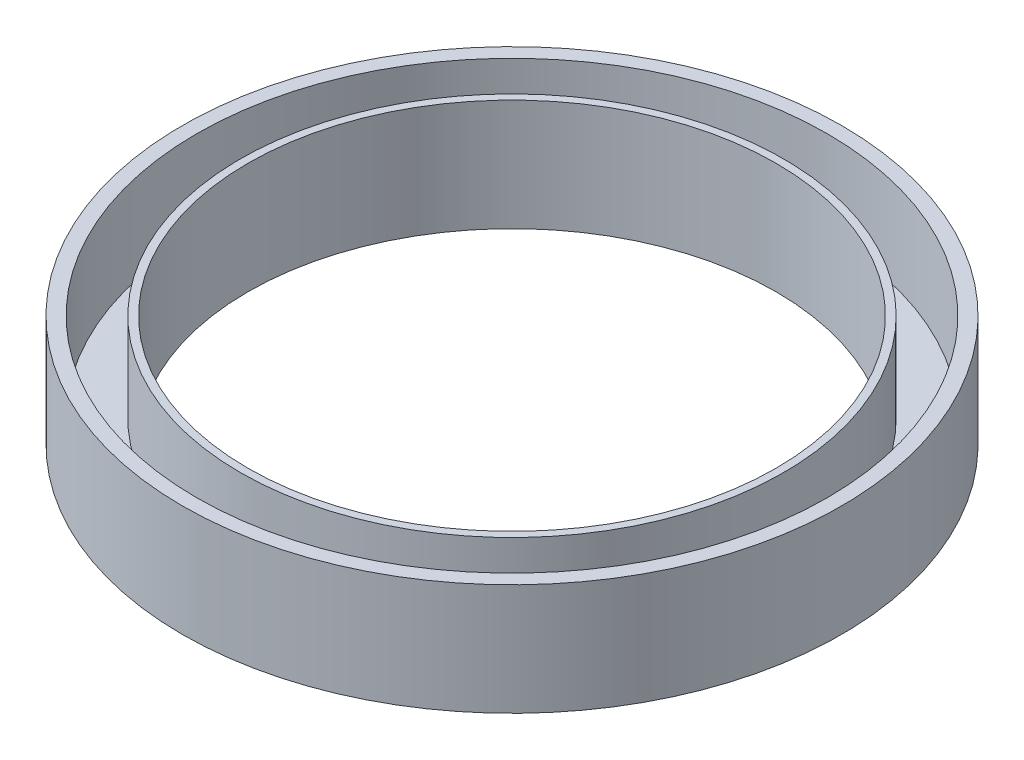
SolidWorks part; units mm, degrees
ref_plane "Alzado" through (0, 0, 0) normal (0, 0, 1) x (1, 0, 0)
ref_plane "Planta" through (0, 0, 0) normal (0, 1, 0) x (1, 0, 0)
ref_plane "Vista lateral" through (0, 0, 0) normal (1, 0, 0) x (0, 0, -1)
sketch "Croquis1" plane through (0, 0, 0) normal (0, 1, 0) x (1, 0, 0)
  circle A0 centre (0, 0) radius 37
  circle A1 centre (0, 0) radius 29.65
  dimension "D1" = 74
  dimension "D2" = 59.3
extrude "Saliente-Extruir1" add sketch "Croquis1" along normal blind 2.5
sketch "Croquis2" plane through (0, 2.5, 0) normal (0, 1, 0) x (1, 0, 0)
  circle A0 centre (0, 0) radius 37
  circle A1 centre (0, 0) radius 35.4
  circle A2 centre (0, 0) radius 29.65
  circle A3 centre (0, 0) radius 30.5
  circle A4 centre (0, 0) radius 37 construction
  circle A5 centre (0, 0) radius 29.65 construction
  circle M5 centre (0, 0) radius 37
  circle M6 centre (0, 0) radius 29.65
  dimension "D1" = 61
  dimension "D2" = 70.8
extrude "Saliente-Extruir2" add sketch "Croquis2" along normal blind 10 contours A1 M5 | A3 M6
